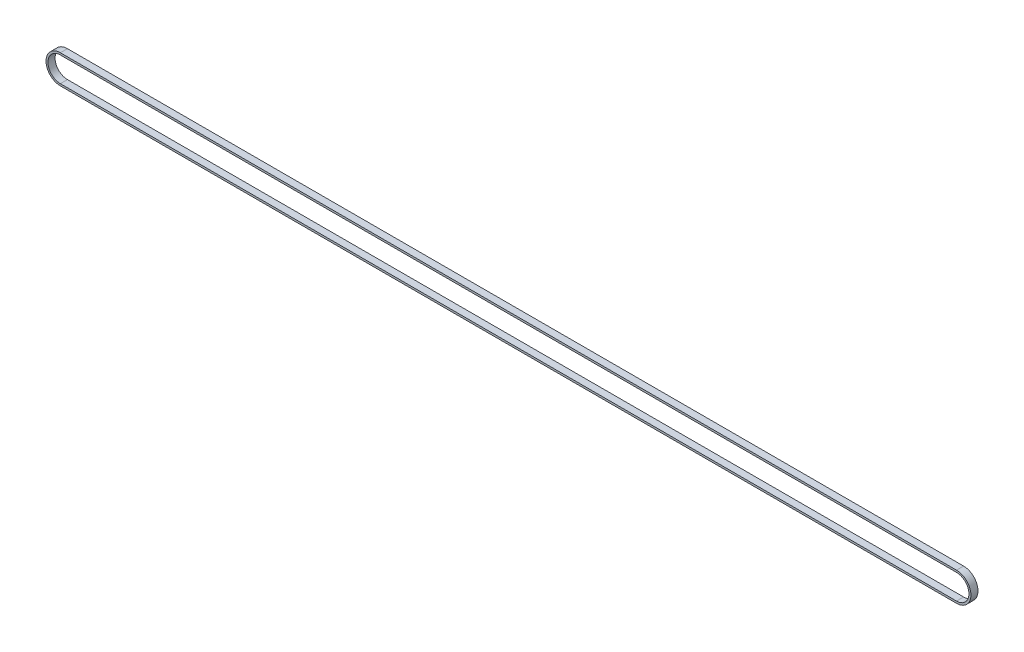
SolidWorks part; units mm, degrees
material "Rubber"
ref_plane "Front Plane" through (0, 0, 0) normal (0, 0, 1) x (1, 0, 0)
ref_plane "Top Plane" through (0, 0, 0) normal (0, 1, 0) x (1, 0, 0)
ref_plane "Right Plane" through (0, 0, 0) normal (1, 0, 0) x (0, 0, -1)
sketch "Sketch1" plane through (0, 0, 0) normal (0, 0, 1) x (1, 0, 0)
  line L0 (0, 0) -> (632, 0) construction
  line L1 (0, 8.75) -> (632, 8.75)
  line L2 (632, -8.75) -> (0, -8.75)
  arc A0 (0, 8.75) -> (0, -8.75) centre (0, 0) ccw
  arc A1 (632, -8.75) -> (632, 8.75) centre (632, 0) ccw
  dimension "D1" = 17.5
  dimension "D2" = 632
extrude "Extrude-Thin1" add sketch "Sketch1" along normal mid plane 5 thin thin type one direction wall 1.38
